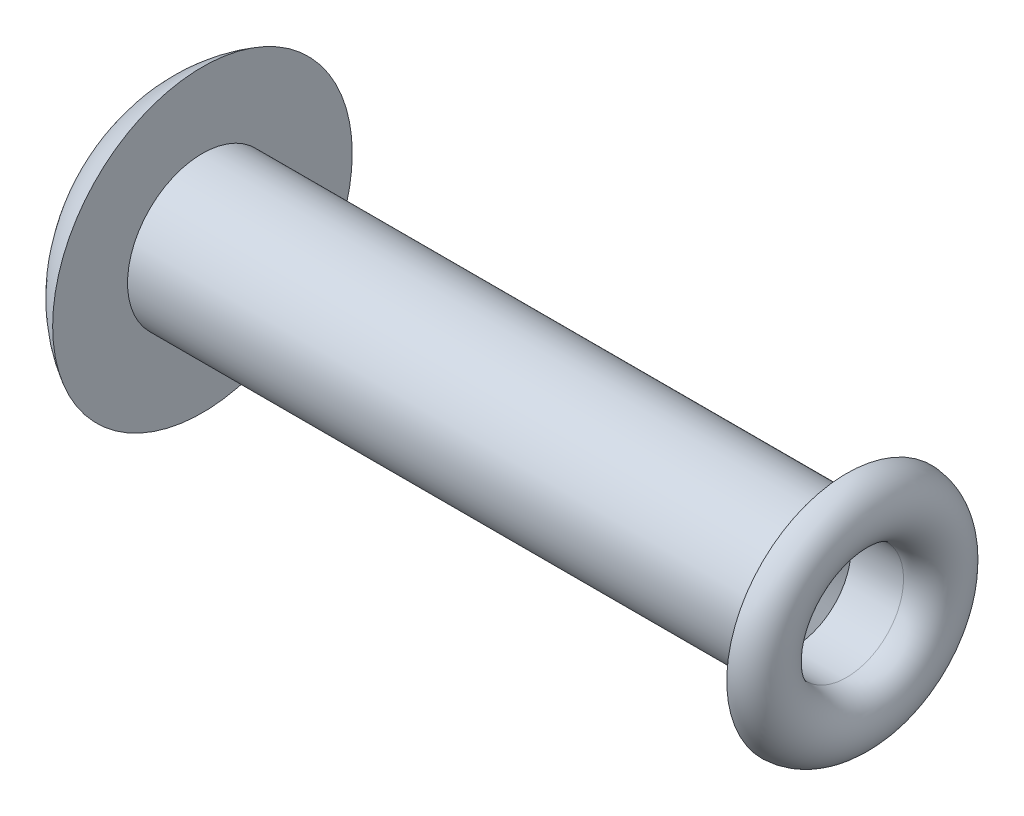
SolidWorks part; units mm, degrees
ref_plane "Plane1" through (0, 0, 0) normal (0, 0, 1) x (1, 0, 0)
ref_plane "Plane2" through (0, 0, 0) normal (0, 1, 0) x (1, 0, 0)
ref_plane "Plane3" through (0, 0, 0) normal (1, 0, 0) x (0, 0, -1)
sketch "Sketch1" plane through (0, 0, 0) normal (0, 0, 1) x (1, 0, 0)
  line L0 (40.3769, 0) -> (-37, 0) construction
  line L1 (0, 8) -> (0, 6.7941)
  line L2 (-0.1025, 5) -> (-43, 5)
  line L3 (-43, 5) -> (-43, 10)
  line L4 (-5.7833, 0) -> (-47.4, 0)
  line L5 (-47.4, 0) -> (-47.4, 2.5)
  line L6 (0, 3.8) -> (-3.5, 3.8)
  line L7 (-3.5, 3.8) -> (-5.7833, 0)
  line L8 (-3.5, -3.8) -> (-5.7833, 0) construction
  line L9 (-0.1025, 5.9) -> (2, 5.9) construction
  line L10 (7, 0) -> (7, 21.0413) construction
  arc A0 (-43, 10) -> (-47.4, 2.5) centre (-38.808, 2.5) ccw
  arc A1 (0, 3.8) -> (0, 8) centre (-0.1025, 5.9) ccw
  arc A2 (-0.1025, 5) -> (0, 6.7941) centre (-0.1025, 5.9) ccw
  dimension "D1" = 118
  dimension "Diameter" = 10
  dimension "GripLength" = 43
  dimension "HeadHt" = 4.4
  dimension "HeadDia" = 20
  dimension "HeadFlat" = 2.5
  dimension "HoleDepth" = 10.5
  dimension "HoleDia" = 7.6
  dimension "HeadKA" = 2
  dimension "HeadDiaA" = 16
  dimension "Length" = 50
revolve "Base-Revolve" add sketch "Sketch1" angle 360 about L0
